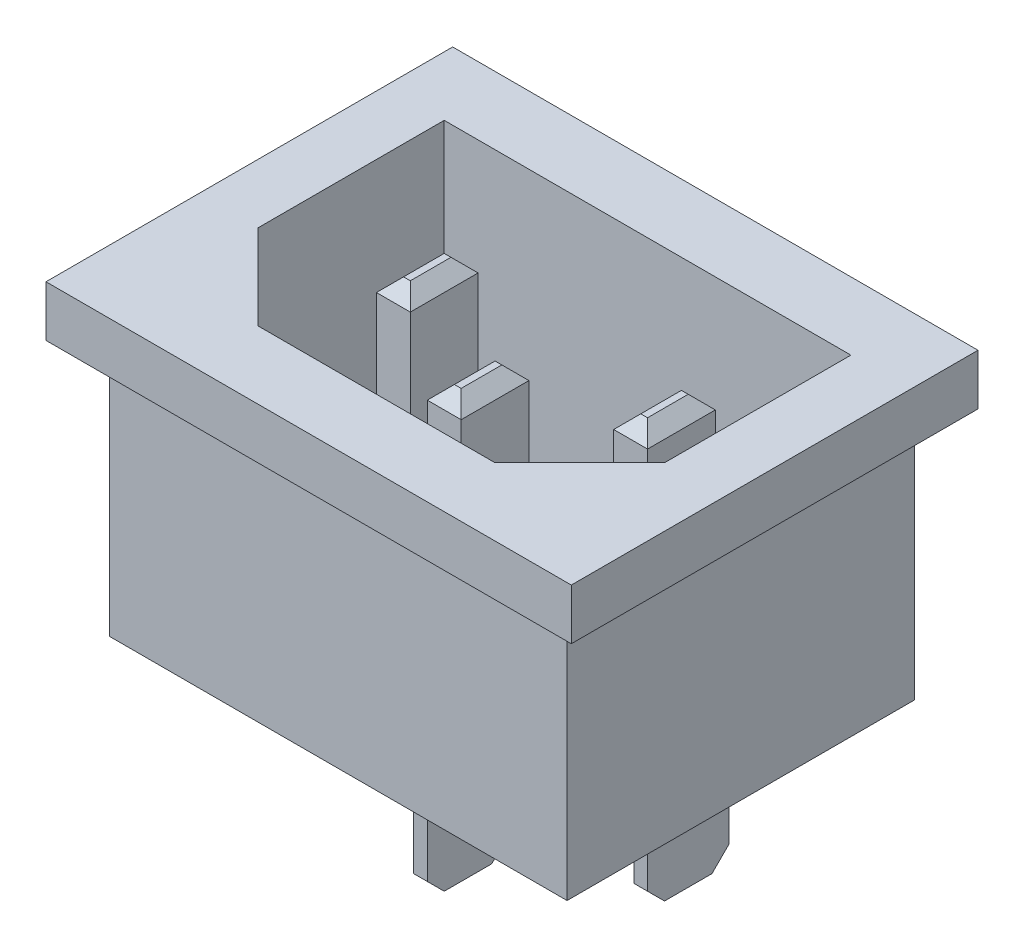
SolidWorks part; units mm, degrees
ref_plane "Спереди" through (0, 0, 0) normal (0, 0, 1) x (1, 0, 0)
ref_plane "Сверху" through (0, 0, 0) normal (0, 1, 0) x (1, 0, 0)
ref_plane "Справа" through (0, 0, 0) normal (1, 0, 0) x (0, 0, -1)
sketch "Эскиз1" plane through (0, 0, 0) normal (0, 1, 0) x (1, 0, 0)
  line L1 (-13.5, -10.25) -> (13.5, -10.25)
  line L2 (-13.5, -10.25) -> (-13.5, 10.25)
  line L3 (-13.5, 10.25) -> (13.5, 10.25)
  line L4 (13.5, -10.25) -> (13.5, 10.25)
  line L5 (-13.5, -10.25) -> (13.5, 10.25) construction
  line L6 (-13.5, 10.25) -> (13.5, -10.25) construction
  point P0 (0, 0)
  dimension "D1" = 20.5
  dimension "D2" = 27
extrude "Бобышка-Вытянуть1" add sketch "Эскиз1" along normal blind 15
sketch "Эскиз2" plane through (0, 0, 0) normal (0, -1, 0) x (1, 0, 0)
  line L0 (0.4, 0.6) -> (0.4, 5.4)
  line L1 (-7.4, -5.4) -> (-6.6, -5.4)
  line L2 (-7.4, -5.4) -> (-7.4, -0.6)
  line L3 (-7.4, -0.6) -> (-6.6, -0.6)
  line L4 (-6.6, -5.4) -> (-6.6, -0.6)
  line L5 (-7.4, -5.4) -> (-6.6, -0.6) construction
  line L6 (-7.4, -0.6) -> (-6.6, -5.4) construction
  line L7 (-0.4, 0.6) -> (-0.4, 5.4)
  line L8 (-0.4, 5.4) -> (0.4, 5.4)
  line L9 (-0.4, 0.6) -> (0.4, 5.4) construction
  line L10 (-0.4, 0.6) -> (0.4, 0.6)
  line L11 (-0.4, 5.4) -> (0.4, 0.6) construction
  line L12 (6.6, -0.6) -> (7.4, -0.6)
  line L13 (6.6, -5.4) -> (7.4, -5.4)
  line L14 (6.6, -5.4) -> (6.6, -0.6)
  line L15 (6.6, -5.4) -> (7.4, -0.6) construction
  line L16 (6.6, -0.6) -> (7.4, -5.4) construction
  line L17 (7.4, -5.4) -> (7.4, -0.6)
  point P0 (-7, -3)
  point P5 (0, 3)
  point P10 (7, -3)
  point P15 (0, 0)
  point P16 (0, 0)
  point P17 (-2.0004, 2.9557)
  point P19 (0, 0)
  dimension "D1" = 0.8
  dimension "D2" = 4.8
  dimension "D3" = 0.8
  dimension "D4" = 4.8
  dimension "D5" = 0.8
  dimension "D6" = 4.8
  dimension "D7" = 14
  dimension "D8" = 7
  dimension "D9" = 6
  dimension "D10" = 3
extrude "Бобышка-Вытянуть2" add sketch "Эскиз2" along normal blind 9
chamfer "Фаска1" distance 1 angle 45 6 edges at (7, -9, -5.4) (7, -9, -0.6) (-7, -9, -5.4) (-7, -9, -0.6) (0, -9, 0.6) (0, -9, 5.4)
sketch "Эскиз3" plane through (0, 15, 0) normal (0, 1, 0) x (1, 0, 0)
  line L1 (15.5, 12) -> (-15.5, 12)
  line L2 (15.5, 12) -> (15.5, -12)
  line L3 (15.5, -12) -> (-15.5, -12)
  line L4 (-15.5, 12) -> (-15.5, -12)
  line L5 (15.5, 12) -> (-15.5, -12) construction
  line L6 (15.5, -12) -> (-15.5, 12) construction
  point P0 (0, 0)
  dimension "D1" = 24
  dimension "D2" = 31
extrude "Бобышка-Вытянуть3" add sketch "Эскиз3" along normal blind 3
sketch "Эскиз4" plane through (0, 18, 0) normal (0, 1, 0) x (1, 0, 0)
  line L0 (12, -3) -> (7, -8)
  line L1 (12, 8) -> (-12, 8)
  line L2 (12, 8) -> (12, -3)
  line L3 (7, -8) -> (-7, -8)
  line L4 (-12, 8) -> (-12, -3)
  line L5 (12, 8) -> (-12, -8) construction
  line L6 (12, -8) -> (-12, 8) construction
  line L7 (-7, -8) -> (-12, -3)
  point P0 (0, 0)
  dimension "D1" = 24
  dimension "D2" = 16
extrude "Вырез-Вытянуть1" cut sketch "Эскиз4" against normal blind 17
sketch "Эскиз5" plane through (0, 1, 0) normal (0, 1, 0) x (1, 0, 0)
  line L0 (8, 0) -> (8, 4)
  line L1 (1, -4) -> (-1, -4)
  line L2 (1, -4) -> (1, 0)
  line L3 (1, 0) -> (-1, 0)
  line L4 (-1, -4) -> (-1, 0)
  line L5 (1, -4) -> (-1, 0) construction
  line L6 (1, 0) -> (-1, -4) construction
  line L7 (8, 4) -> (6, 0) construction
  line L8 (8, 0) -> (6, 4) construction
  line L9 (8, 0) -> (6, 0)
  line L10 (8, 4) -> (6, 4)
  line L11 (6, 0) -> (6, 4)
  line L12 (-6, 0) -> (-8, 4) construction
  line L13 (-6, 4) -> (-8, 0) construction
  line L14 (-8, 0) -> (-8, 4)
  line L15 (-6, 4) -> (-8, 4)
  line L16 (-6, 0) -> (-6, 4)
  line L17 (-6, 0) -> (-8, 0)
  point P0 (0, -2)
  point P5 (7, 2)
  point P11 (-7, 2)
  point P16 (0, 0)
  point P17 (0, 0)
  point P19 (0, 0)
  point P22 (-7.1281, 2)
  dimension "D1" = 2
  dimension "D2" = 4
  dimension "D3" = 2
  dimension "D4" = 4
  dimension "D5" = 2
  dimension "D6" = 4
  dimension "D7" = 4
  dimension "D8" = 2
  dimension "D9" = 7
  dimension "D10" = 14
extrude "Бобышка-Вытянуть4" add sketch "Эскиз5" along normal blind 15
chamfer "Фаска2" distance 0.8 angle 45 12 edges at (0, 16, 0) (1, 16, 2) (0, 16, 4) (-1, 16, 2) (-6, 16, -2) (-7, 16, 0) (-8, 16, -2) (-7, 16, -4) (7, 16, -4) (8, 16, -2) (6, 16, -2) (7, 16, 0)
